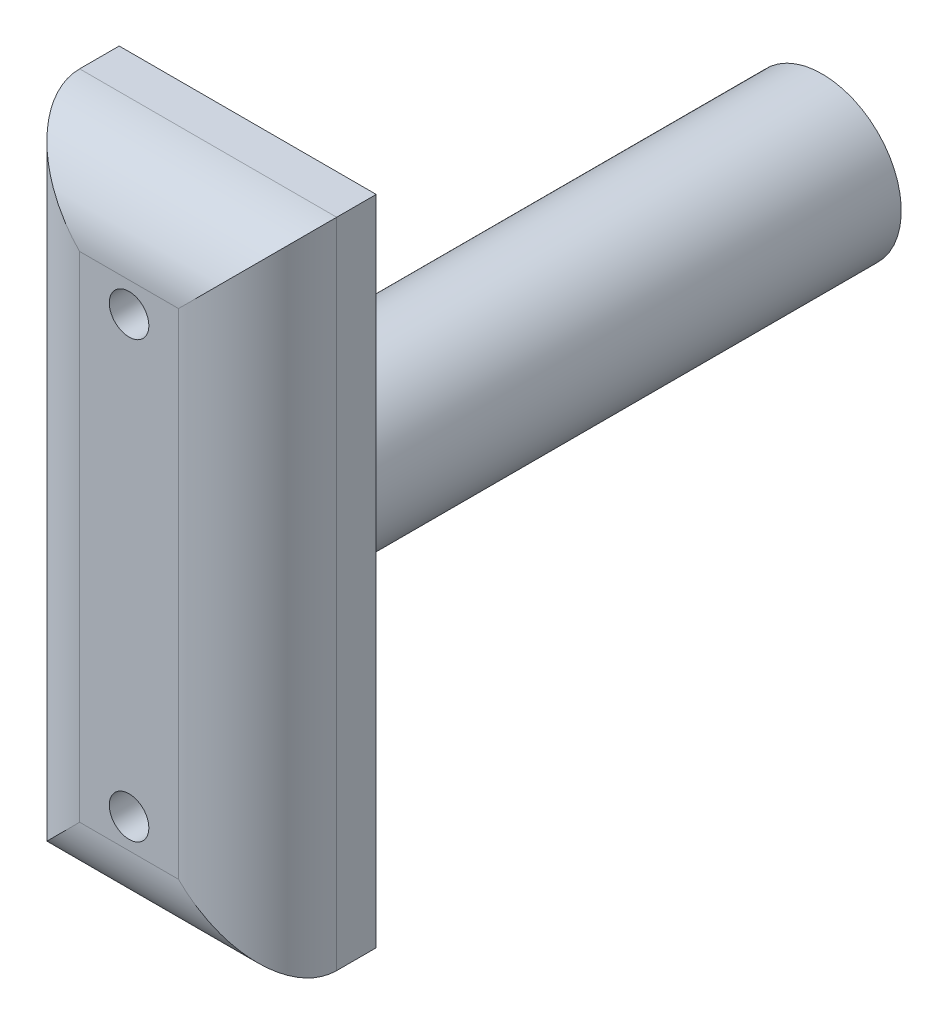
SolidWorks part; units mm, degrees
ref_plane "Front Plane" through (0, 0, 0) normal (0, 0, 1) x (1, 0, 0)
ref_plane "Top Plane" through (0, 0, 0) normal (0, 1, 0) x (1, 0, 0)
ref_plane "Right Plane" through (0, 0, 0) normal (1, 0, 0) x (0, 0, -1)
sketch "Sketch1" plane through (0, 0, 0) normal (0, 0, 1) x (1, 0, 0)
  line L1 (6.5, -16.5) -> (-6.5, -16.5)
  line L2 (6.5, -16.5) -> (6.5, 16.5)
  line L3 (6.5, 16.5) -> (-6.5, 16.5)
  line L4 (-6.5, -16.5) -> (-6.5, 16.5)
  line L5 (6.5, -16.5) -> (-6.5, 16.5) construction
  line L6 (6.5, 16.5) -> (-6.5, -16.5) construction
  point P0 (0, 0)
  dimension "D1" = 33
  dimension "D2" = 13
extrude "Boss-Extrude1" add sketch "Sketch1" along normal blind 6
sketch "Sketch2" plane through (0, 0, 0) normal (0, 0, -1) x (-1, 0, 0)
  circle A0 centre (0, 0) radius 4
  dimension "D1" = 8
extrude "Boss-Extrude2" add sketch "Sketch2" along normal blind 29.056
sketch "Sketch3" plane through (0, 0, 6) normal (0, 0, 1) x (1, 0, 0)
  circle A0 centre (0, 11) radius 1
  circle A1 centre (0, -11) radius 1
  point P4 (0, 0)
  dimension "D1" = 2
  dimension "D2" = 11
  dimension "D3" = 11
extrude "Cut-Extrude1" cut sketch "Sketch3" against normal up to next
fillet "Fillet1" radius 4 4 edges at (-6.5, 0, 6) (6.5, 0, 6) (0, -16.5, 6) (0, 16.5, 6)
